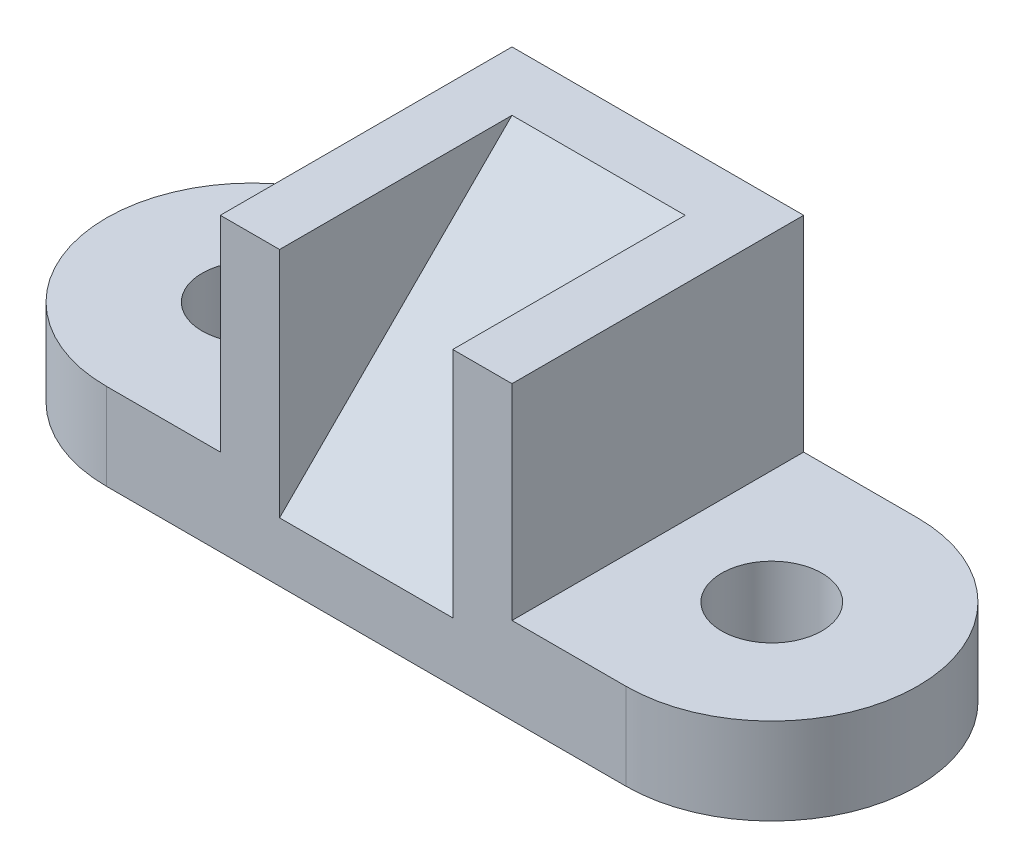
SolidWorks part; units mm, degrees
ref_plane "Front Plane" through (0, 0, 0) normal (0, 0, 1) x (1, 0, 0)
ref_plane "Top Plane" through (0, 0, 0) normal (0, 1, 0) x (1, 0, 0)
ref_plane "Right Plane" through (0, 0, 0) normal (1, 0, 0) x (0, 0, -1)
sketch "Sketch1" plane through (0, 0, 0) normal (0, 1, 0) x (1, 0, 0)
  line L0 (0, 0) -> (-57, 0)
  line L1 (-57, 64) -> (0, 64)
  line L2 (0, 64) -> (0, 0)
  arc A0 (-57, 64) -> (-57, 0) centre (-57, 32) ccw
  circle A1 centre (-57, 32) radius 11
  dimension "D2" = 64
  dimension "D3" = 22
  dimension "D1" = 57
extrude "Boss-Extrude1" add sketch "Sketch1" along normal blind 19
sketch "Sketch2" plane through (0, 19, 0) normal (0, 1, 0) x (1, 0, 0)
  line L0 (0, 64) -> (0, 0)
  line L1 (0, 0) -> (-32, 0)
  line L2 (-57, 0) -> (0, 0) construction
  line L3 (-32, 0) -> (-32, 64)
  line L4 (0, 64) -> (-57, 64) construction
  line L5 (-32, 64) -> (0, 64)
  dimension "D1" = 32
extrude "Boss-Extrude2" add sketch "Sketch2" along normal blind 45
sketch "Sketch3" plane through (0, 0, 0) normal (1, 0, 0) x (0, 0, -1)
  line L0 (51, 64) -> (51, 13)
  line L1 (0, 64) -> (64, 64) construction
  line L2 (51, 13) -> (64, 13)
  line L3 (64, 64) -> (64, 0) construction
  line L4 (64, 13) -> (64, 64)
  line L5 (64, 64) -> (51, 64)
  line L6 (0, 64) -> (51, 64)
  line L7 (0, 64) -> (0, 13)
  line L8 (0, 64) -> (0, 0) construction
  line L9 (0, 13) -> (51, 64)
  dimension "D1" = 13
  dimension "D2" = 51
extrude "Cut-Extrude2" cut sketch "Sketch3" against normal blind 19 contours L3 L9 L1
ref_plane "Plane1" through (0, 0, 0) normal (1, 0, 0) x (0, 0, -1)
mirror "Mirror1" about plane through (0, 0, 0) normal (1, 0, 0) of "Boss-Extrude2", "Boss-Extrude1", "Cut-Extrude2"
